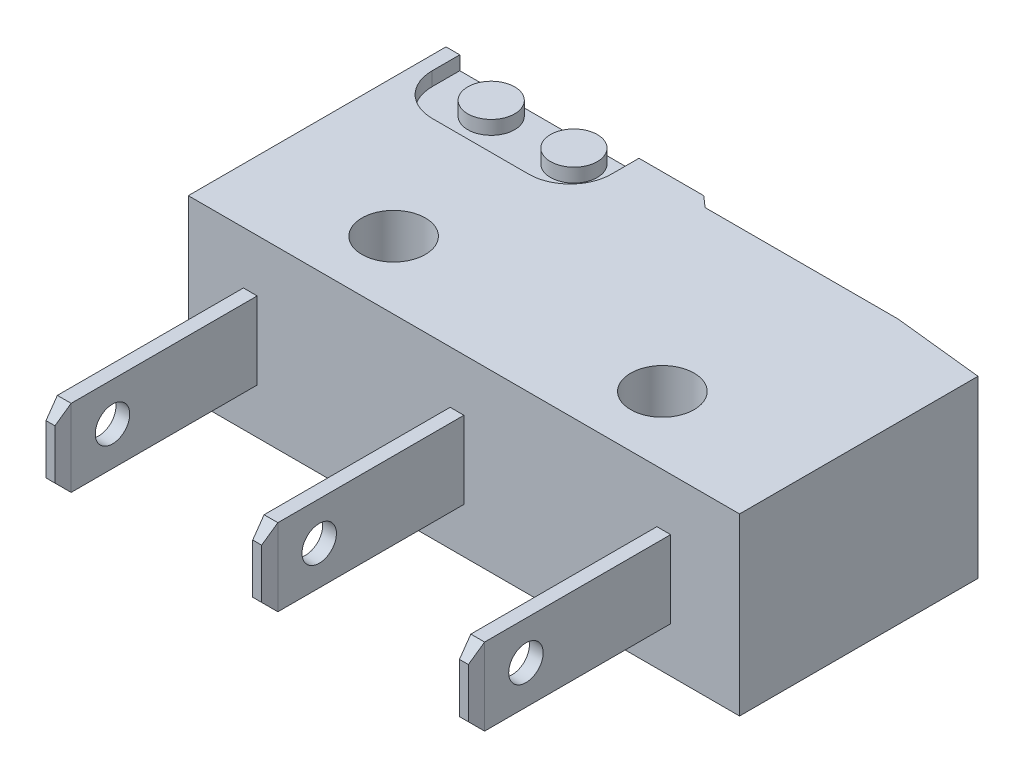
SolidWorks part; units mm, degrees
ref_plane "Front Plane" through (0, 0, 0) normal (0, 0, 1) x (1, 0, 0)
ref_plane "Top Plane" through (0, 0, 0) normal (0, 1, 0) x (1, 0, 0)
ref_plane "Right Plane" through (0, 0, 0) normal (1, 0, 0) x (0, 0, -1)
sketch "Sketch1" plane through (0, 0, 0) normal (0, 1, 0) x (1, 0, 0)
  line L0 (9.35, 9.35) -> (9.75, 9)
  line L1 (0, 0) -> (20, 0)
  line L2 (0, 0) -> (0, 9.35)
  line L3 (0, 9.35) -> (9.35, 9.35)
  line L4 (20, 0) -> (20, 8.65)
  line L5 (9.75, 9) -> (16.75, 9)
  line L6 (16.75, 9) -> (20, 8.65)
  dimension "D1" = 9.35
  dimension "D2" = 20
  dimension "D3" = 9
  dimension "D4" = 9.35
  dimension "D5" = 9.75
  dimension "D6" = 8.65
  dimension "D7" = 7
extrude "Boss-Extrude1" add sketch "Sketch1" along normal blind 6.35
sketch "Sketch2" plane through (0, 6.35, 0) normal (0, 1, 0) x (1, 0, 0)
  line L0 (20, 0) -> (20, 8.65) construction
  line L1 (0, 9.35) -> (0, 0) construction
  line L2 (0, 0) -> (20, 0) construction
  circle A0 centre (14.75, 2.45) radius 1.15
  circle A1 centre (5, 2.45) radius 1.15
  dimension "D1" = 2.3
  dimension "D2" = 2.3
  dimension "D3" = 5.25
  dimension "D4" = 5
  dimension "D5" = 2.45
  dimension "D6" = 2.45
extrude "Cut-Extrude1" cut sketch "Sketch2" against normal blind 6.35
sketch "Sketch3" plane through (0, 0, 0) normal (0, 0, 1) x (1, 0, 0)
  line L0 (0, 6.35) -> (0, 0) construction
  line L1 (2.5, 4.45) -> (2, 4.45)
  line L2 (2.5, 4.45) -> (2.5, 1.65)
  line L3 (2.5, 1.65) -> (2, 1.65)
  line L4 (2, 4.45) -> (2, 1.65)
  line L5 (9.5, 4.45) -> (10, 4.45)
  line L6 (9.5, 4.45) -> (9.5, 1.65)
  line L7 (9.5, 1.65) -> (10, 1.65)
  line L8 (10, 4.45) -> (10, 1.65)
  line L9 (17, 4.45) -> (17.5, 4.45)
  line L10 (17, 4.45) -> (17, 1.65)
  line L11 (17, 1.65) -> (17.5, 1.65)
  line L12 (17.5, 4.45) -> (17.5, 1.65)
  line L13 (0, 6.35) -> (20, 6.35) construction
  dimension "D1" = 2.8
  dimension "D2" = 2.8
  dimension "D3" = 2.8
  dimension "D4" = 0.5
  dimension "D5" = 0.5
  dimension "D6" = 0.5
  dimension "D7" = 7
  dimension "D8" = 7
  dimension "D9" = 2
  dimension "D10" = 1.9
extrude "Boss-Extrude2" add sketch "Sketch3" along normal blind 7.25
sketch "Sketch4" plane through (2, 0, 0) normal (-1, 0, 0) x (0, 0, 1)
  line L0 (7.25, 4.45) -> (7.25, 1.65) construction
  line L1 (7.25, 4.45) -> (0, 4.45) construction
  circle A0 centre (5.25, 3.05) radius 0.625
  dimension "D1" = 2
  dimension "D2" = 1.4
extrude "Cut-Extrude2" cut sketch "Sketch4" against normal blind 16.25
chamfer "Chamfer1" distance 0.5 angle 45 6 edges at (17.25, 1.65, 7.25) (9.75, 1.65, 7.25) (2.25, 1.65, 7.25) (2.25, 4.45, 7.25) (9.75, 4.45, 7.25) (17.25, 4.45, 7.25)
chamfer "Chamfer2" distance 0.5 angle 10 6 edges at (2.5, 3.05, 7.25) (2, 3.05, 7.25) (9.5, 3.05, 7.25) (10, 3.05, 7.25) (17, 3.05, 7.25) (17.5, 3.05, 7.25)
sketch "Sketch5" plane through (0, 6.35, 0) normal (0, 1, 0) x (1, 0, 0)
  line L0 (9.35, 9.35) -> (0, 9.35) construction
  line L1 (0.5, 9.35) -> (7, 9.35)
  line L2 (0.5, 9.35) -> (0.5, 6.85)
  line L3 (0.5, 6.85) -> (7, 6.85)
  line L4 (7, 9.35) -> (7, 6.85)
  line L5 (0, 9.35) -> (0, 0) construction
  circle A0 centre (2.5, 8.49) radius 0.85
  circle A1 centre (5.5, 8.49) radius 0.85
  dimension "D4" = 1.7
  dimension "D5" = 0.86
  dimension "D1" = 2.5
  dimension "D2" = 6.5
  dimension "D3" = 0.5
  dimension "D6" = 0.86
  dimension "D7" = 3
  dimension "D8" = 2
extrude "Cut-Extrude4" cut sketch "Sketch5" against normal blind 0.5
ref_plane "Plane1" through (0, 3.175, 0) normal (0, -1, 0) x (-1, 0, 0)
mirror "Mirror1" about plane through (0, 3.175, 0) normal (0, -1, 0) of "Cut-Extrude4"
fillet "Fillet1" radius 1.5 4 edges at (7, 6.1, -6.85) (0.5, 6.1, -6.85) (0.5, 0.25, -6.85) (7, 0.25, -6.85)
